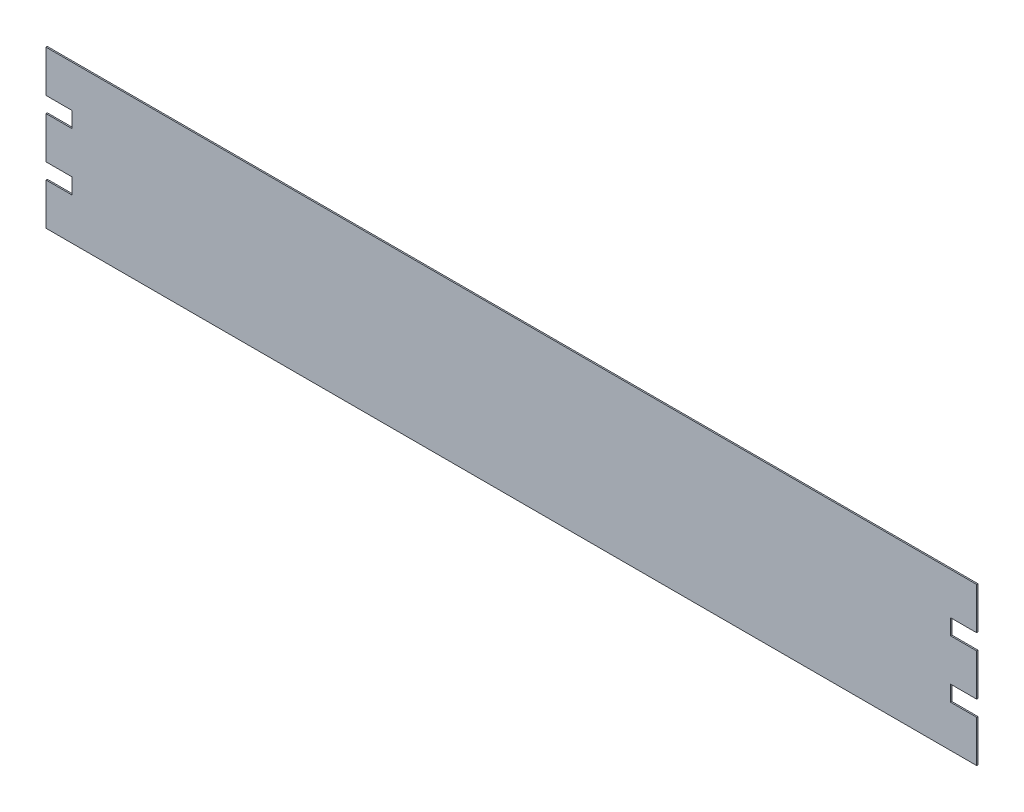
SolidWorks part; units mm, degrees
material "Hexcel AS4C (3000 Filaments)"
ref_plane "Front Plane" through (0, 0, 0) normal (0, 0, 1) x (1, 0, 0)
ref_plane "Top Plane" through (0, 0, 0) normal (0, 1, 0) x (1, 0, 0)
ref_plane "Right Plane" through (0, 0, 0) normal (1, 0, 0) x (0, 0, -1)
sketch "Sketch2" plane through (0, 0, 0) normal (0, 0, 1) x (1, 0, 0)
  line L0 (0, 0) -> (5, 0)
  line L1 (5, 0) -> (173, 20)
  line L2 (173, 20) -> (178, 20)
  line L3 (178, 20) -> (178, 50)
  line L4 (178, 50) -> (0, 50)
  line L5 (0, 50) -> (0, 0)
  dimension "D1" = 50
  dimension "D2" = 5
  dimension "D3" = 5
  dimension "D4" = 168
  dimension "D5" = 30
extrude "Boss-Extrude1" add sketch "Sketch2" along normal mid plane 0.25
sketch "Sketch4" plane through (0, 0, 0.125) normal (0, 0, 1) x (1, 0, 0)
  line L0 (178, 20) -> (178, 50) construction
  line L1 (178, 42) -> (173, 42)
  line L2 (178, 42) -> (178, 39)
  line L3 (178, 39) -> (173, 39)
  line L4 (173, 42) -> (173, 39)
  line L5 (178, 50) -> (0, 50) construction
  dimension "D1" = 5
  dimension "D2" = 3
  dimension "D3" = 8
extrude "Cut-Extrude2" cut sketch "Sketch4" against normal through all
pattern_linear "LPattern3" count 4 spacing 11 along (0, -1, 0) count 2 spacing 173 along (-1, 0, 0) of "Cut-Extrude2"
sketch "Sketch5" plane through (0, 0, 0.125) normal (0, 0, 1) x (1, 0, 0)
  line L1 (178, 20) -> (0, 20)
  line L2 (178, 20) -> (178, 0)
  line L3 (178, 0) -> (0, 0)
  line L4 (0, 20) -> (0, 0)
extrude "Cut-Extrude3" cut sketch "Sketch5" against normal through all
